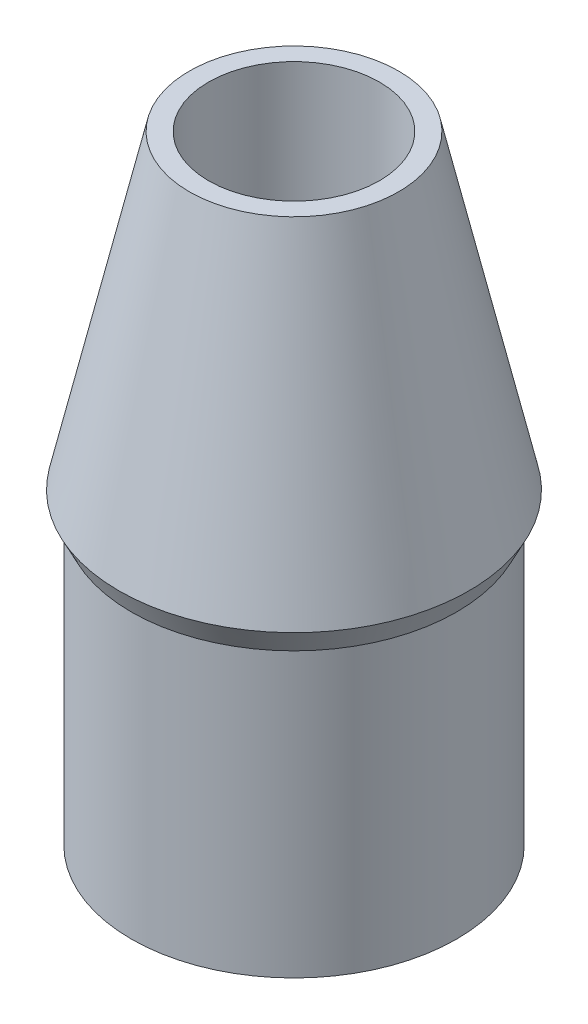
SolidWorks part; units mm, degrees
ref_plane "Front Plane" through (0, 0, 0) normal (0, 0, 1) x (1, 0, 0)
ref_plane "Top Plane" through (0, 0, 0) normal (0, 1, 0) x (1, 0, 0)
ref_plane "Right Plane" through (0, 0, 0) normal (1, 0, 0) x (0, 0, -1)
sketch "Sketch3" plane through (0, 0, 0) normal (0, 0, 1) x (1, 0, 0)
  line L0 (0, 16.51) -> (0, -13.97) construction
  line L1 (8.0264, -13.97) -> (0, -13.97)
  line L2 (5.1599, 16.51) -> (0, 16.51)
  line L3 (0, 16.51) -> (0, -13.97)
  line L7 (8.0264, 0) -> (8.0264, -13.97)
  line L10 (8.0264, 0) -> (8.6308, 1.204)
  line L11 (8.6308, 1.204) -> (5.1599, 16.51)
  dimension "D1" = 16.51
  dimension "D2" = 13.97
  dimension "D3" = 8.0264
revolve "Revolve1" add sketch "Sketch3" angle 360 about L0
hole_wizard "3/8-24 Tapped Hole1" positions "Sketch5" profile "Sketch4" tap size "3/8-24" standard "ANSI Inch"
sketch "Sketch5" plane through (0, 16.51, 0) normal (0, 1, 0) x (1, 0, 0)
  point P0 (0, 0)
sketch "Sketch4" plane through (0, 16.51, 0) normal (1, 0, 0) x (0, 0, 1)
  line L0 (0, 0) -> (0, 26.8794)
  line L1 (0, 26.8794) -> (4.2164, 24.3459)
  line L2 (4.2164, 24.3459) -> (4.2164, 0)
  line L5 (4.2164, 0) -> (0, 0)
  line L10 (0, 26.8794) -> (-4.2164, 24.3459) construction
  line L11 (0, -6.35) -> (0, 107.95) construction
  dimension "Tap Drill Dia." = 8.4328
  dimension "Tap Drill Depth" = 24.3459
  dimension "Drill Angle" = 118
cosmetic thread "Hole Thread1" parameters "D1"=19.05, "D2"=9.525
